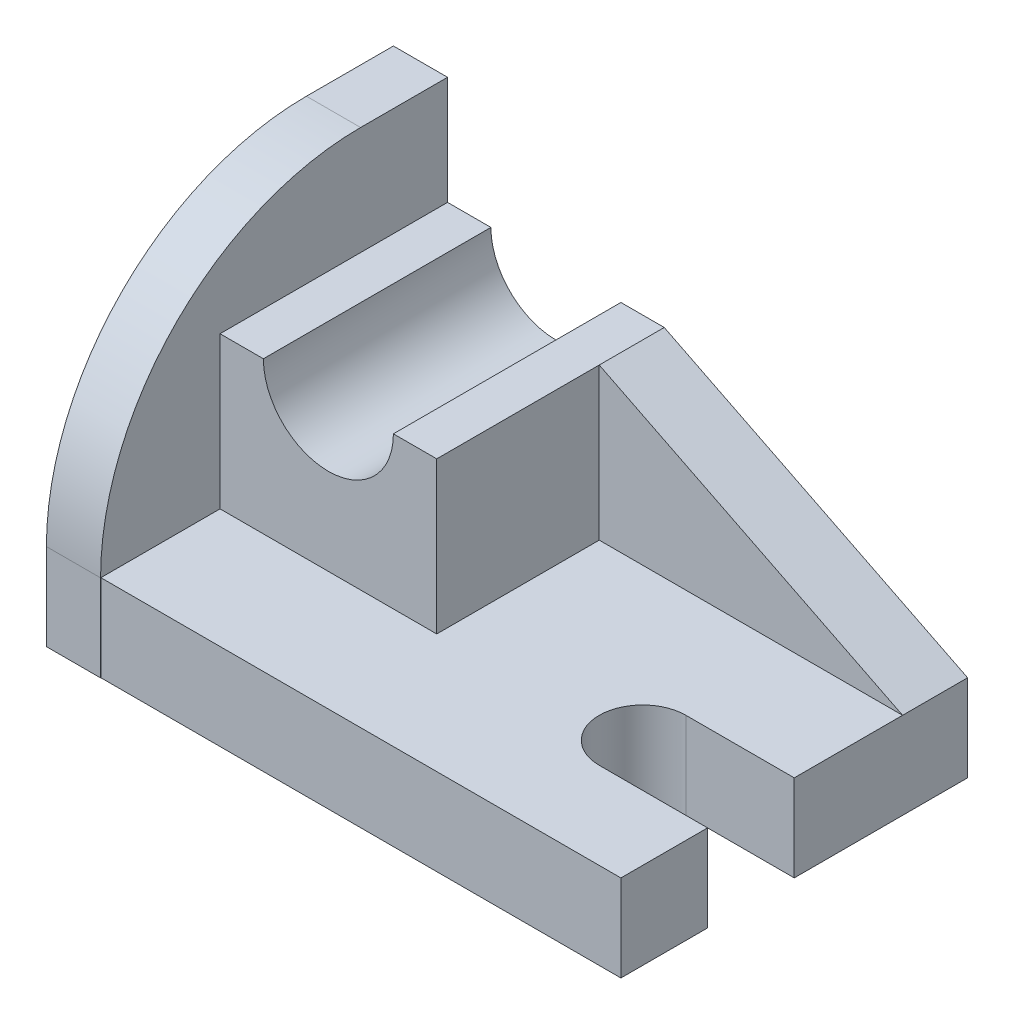
SolidWorks part; units mm, degrees
ref_plane "Front Plane" through (0, 0, 0) normal (0, 0, 1) x (1, 0, 0)
ref_plane "Top Plane" through (0, 0, 0) normal (0, 1, 0) x (1, 0, 0)
ref_plane "Right Plane" through (0, 0, 0) normal (1, 0, 0) x (0, 0, -1)
sketch "Sketch2" plane through (0, 0, 0) normal (0, 1, 0) x (1, 0, 0)
  line L1 (13.0745, -527.3394) -> (2451.4745, -527.3394)
  line L2 (13.0745, -527.3394) -> (13.0745, 1098.2606)
  line L3 (13.0745, 1098.2606) -> (2451.4745, 1098.2606)
  line L4 (2451.4745, -527.3394) -> (2451.4745, 1098.2606)
  dimension "D1" = 2438.4
  dimension "D2" = 1625.6
extrude "Boss-Extrude1" add sketch "Sketch2" along normal blind 406.4
sketch "Sketch4" plane through (0, 406.4, 0) normal (0, 1, 0) x (1, 0, 0)
  line L0 (2451.4745, 82.2606) -> (1943.4745, 82.2606) construction
  line L1 (2451.4745, -120.9394) -> (1943.4745, -120.9394)
  line L2 (2451.4745, 285.4606) -> (1943.4745, 285.4606)
  arc A0 (2451.4745, -120.9394) -> (2451.4745, 285.4606) centre (2451.4745, 82.2606) ccw
  arc A1 (1943.4745, 285.4606) -> (1943.4745, -120.9394) centre (1943.4745, 82.2606) ccw
  point P2 (2197.4745, 82.2606)
  dimension "D1" = 406.4
  dimension "D2" = 508
  dimension "D3" = 406.4
extrude "Cut-Extrude1" cut sketch "Sketch4" against normal through all
sketch "Sketch6" plane through (13.0745, 0, 0) normal (-1, 0, 0) x (0, 0, 1)
  line L1 (-1098.2606, 0) -> (528.7224, 0)
  line L2 (-1098.2606, 0) -> (-1098.2606, 1625.6)
  line L3 (-1098.2606, 1625.6) -> (-690.4776, 1625.6)
  line L4 (528.7224, 0) -> (528.7224, 406.4)
  arc A0 (-690.4776, 1625.6) -> (528.7224, 406.4) centre (-690.4776, 406.4) cw
  point P6 (528.7224, 1625.6)
  dimension "D3" = 1219.2
  dimension "D1" = 1625.6
  dimension "D2" = 1626.983
extrude "Boss-Extrude3" add sketch "Sketch6" along normal blind 254
sketch "Sketch8" plane through (0, 406.4, 0) normal (0, 1, 0) x (1, 0, 0)
  line L0 (13.0745, -527.3394) -> (2451.4745, -527.3394) construction
  line L1 (13.0745, 1098.2606) -> (1029.0745, 1098.2606)
  line L2 (13.0745, 1098.2606) -> (13.0745, 31.4606)
  line L3 (13.0745, 31.4606) -> (1029.0745, 31.4606)
  line L4 (1029.0745, 1098.2606) -> (1029.0745, 31.4606)
  dimension "D1" = 1016
  dimension "D2" = 558.8
  dimension "D3" = 1066.8
  dimension "D4" = 1066.8
extrude "Boss-Extrude4" add sketch "Sketch8" along normal blind 711.2
sketch "Sketch9" plane through (0, 0, -31.4606) normal (0, 0, 1) x (1, 0, 0)
  circle A0 centre (521.0745, 1117.6) radius 304.8
  dimension "D1" = 609.6
extrude "Cut-Extrude3" cut sketch "Sketch9" against normal through all
sketch "Sketch12" plane through (0, 0, -1098.2606) normal (0, 0, -1) x (-1, 0, 0)
  line L0 (-2451.4745, 406.4) -> (-1029.0745, 1117.6)
  line L2 (-2451.4745, 406.4) -> (-1029.0745, 406.4)
  line L3 (-1029.0745, 406.4) -> (-1029.0745, 1117.6)
extrude "Boss-Extrude6" add sketch "Sketch12" against normal blind 304.8 contours L3 L0 L2
